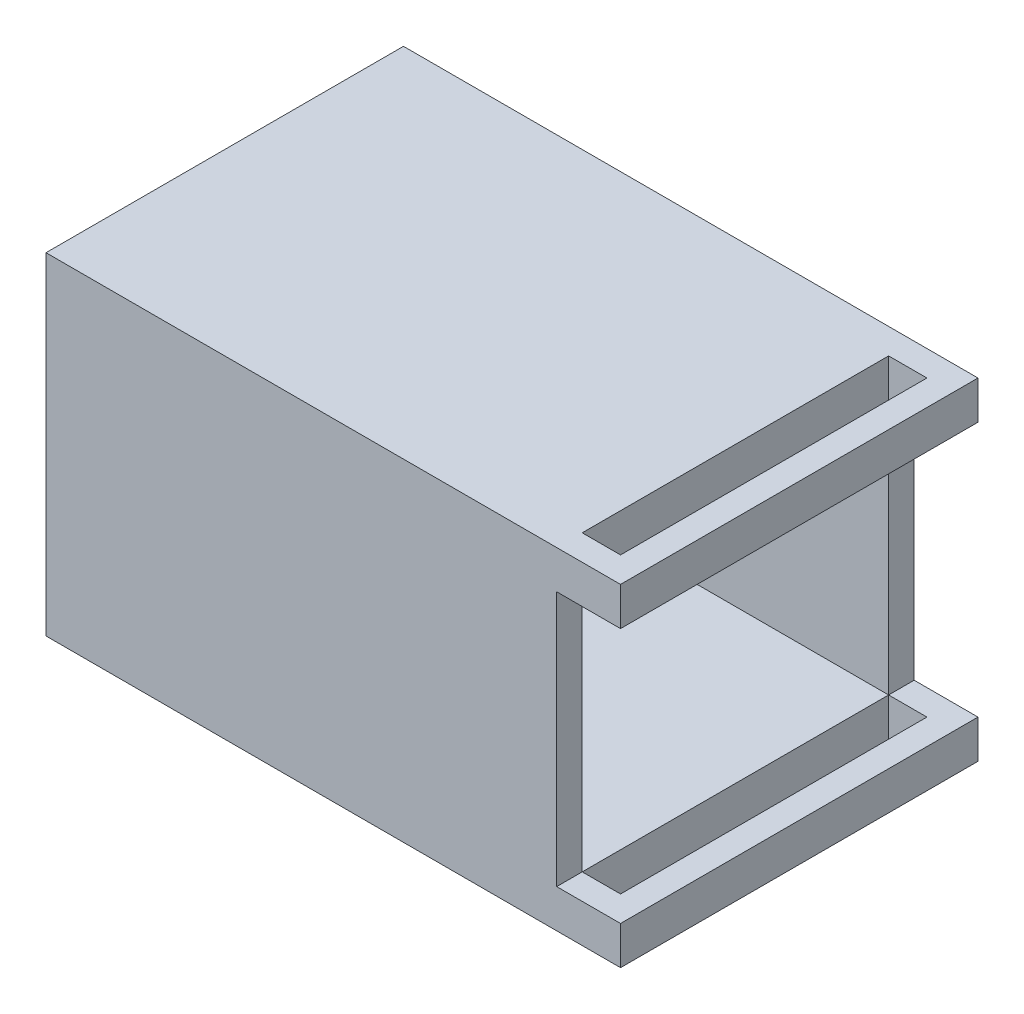
SolidWorks part; units mm, degrees
ref_plane "Front Plane" through (0, 0, 0) normal (0, 0, 1) x (1, 0, 0)
ref_plane "Top Plane" through (0, 0, 0) normal (0, 1, 0) x (1, 0, 0)
ref_plane "Right Plane" through (0, 0, 0) normal (1, 0, 0) x (0, 0, -1)
sketch "Sketch1" plane through (0, 0, 0) normal (0, 1, 0) x (1, 0, 0)
  line L1 (0, 0) -> (45, 0)
  line L2 (0, 0) -> (0, 28)
  line L3 (0, 28) -> (45, 28)
  line L4 (45, 0) -> (45, 28)
  dimension "D1" = 28
  dimension "D2" = 45
extrude "Boss-Extrude1" add sketch "Sketch1" along normal blind 3 contours L2 L1 L4 L3
sketch "Sketch2" plane through (0, 3, 0) normal (0, 1, 0) x (1, 0, 0)
  line L0 (40, 26) -> (40, 28)
  line L1 (0, 28) -> (40, 28)
  line L2 (0, 28) -> (0, 0)
  line L3 (0, 0) -> (40, 0)
  line L5 (2, 26) -> (40, 26)
  line L6 (2, 26) -> (2, 2)
  line L7 (2, 2) -> (40, 2)
  line L9 (40, 2) -> (40, 0)
  line L10 (45, 0) -> (45, 28) construction
  line L11 (0, 0) -> (45, 0) construction
  dimension "D1" = 2
  dimension "D2" = 2
  dimension "D3" = 2
  dimension "D4" = 5
  dimension "D5" = 5
extrude "Boss-Extrude2" add sketch "Sketch2" along normal blind 22 contours L5 L0 L1 L2 L3 L9 L7 L6
sketch "Sketch4" plane through (0, 25, 0) normal (0, 1, 0) x (1, 0, 0)
  line L0 (0, 28) -> (40, 28) construction
  line L1 (0, 28) -> (45, 28)
  line L2 (0, 28) -> (0, 0)
  line L3 (0, 0) -> (45, 0)
  line L4 (45, 28) -> (45, 0)
  line L5 (2, 2) -> (40, 2) construction
  line L6 (40, 26) -> (43, 26)
  line L7 (40, 26) -> (40, 2)
  line L8 (40, 2) -> (43, 2)
  line L9 (43, 26) -> (43, 2)
  dimension "D1" = 2
extrude "Boss-Extrude4" add sketch "Sketch4" against normal blind 2
sketch "Sketch5" plane through (0, 0, 0) normal (-1, 0, 0) x (0, 0, 1)
  line L0 (-18.72, 5.25) -> (-18.72, 6.16)
  line L1 (-17.47, 4) -> (-10.53, 4)
  line L2 (-17.47, 7.41) -> (-10.53, 7.41)
  line L3 (-9.28, 6.16) -> (-9.28, 5.25)
  line L4 (0, 0) -> (-28, 0) construction
  line L5 (-28, 25) -> (-28, 0) construction
  line L6 (0, 25) -> (0, 0) construction
  line L7 (-18.5, 12.5) -> (-9.5, 12.5)
  line L8 (-18.5, 12.5) -> (-18.5, 8.5)
  line L9 (-18.5, 8.5) -> (-9.5, 8.5)
  line L10 (-9.5, 12.5) -> (-9.5, 8.5)
  arc A0 (-18.72, 5.25) -> (-17.47, 4) centre (-17.47, 5.25) ccw
  arc A1 (-17.47, 7.41) -> (-18.72, 6.16) centre (-17.47, 6.16) ccw
  arc A2 (-9.28, 6.16) -> (-10.53, 7.41) centre (-10.53, 6.16) ccw
  arc A3 (-10.53, 4) -> (-9.28, 5.25) centre (-10.53, 5.25) ccw
  dimension "D7" = 1.25
  dimension "D1" = 1.25
  dimension "D2" = 0.91
  dimension "D3" = 6.94
  dimension "D4" = 1.25
  dimension "D5" = 1.25
  dimension "D6" = 6.94
  dimension "D8" = 3.41
  dimension "D9" = 0.91
  dimension "D10" = 4
  dimension "D11" = 9.28
  dimension "D12" = 4
  dimension "D13" = 9
  dimension "D14" = 1.09
  dimension "D15" = 0.22
  dimension "D16" = 0.22
  dimension "D17" = 9.28
extrude "Cut-Extrude1" cut sketch "Sketch5" against normal blind 2
sketch "Sketch6" plane through (0, 3, 0) normal (0, 1, 0) x (1, 0, 0)
  line L0 (45, 0) -> (45, 28) construction
  line L1 (43, 2) -> (40, 2)
  line L2 (43, 2) -> (43, 26)
  line L3 (43, 26) -> (40, 26)
  line L4 (40, 2) -> (40, 26)
  line L5 (40, 0) -> (45, 0) construction
  line L6 (40, 28) -> (45, 28) construction
  line L7 (40, 26) -> (40, 28) construction
  dimension "D1" = 2
  dimension "D2" = 2
  dimension "D3" = 2
extrude "Cut-Extrude2" cut sketch "Sketch6" against normal blind 3
sketch "Sketch7" plane through (0, 25, 0) normal (0, 1, 0) x (1, 0, 0)
  line L1 (0, 0) -> (45, 0)
  line L2 (0, 0) -> (0, 28)
  line L3 (0, 28) -> (45, 28)
  line L4 (45, 0) -> (45, 28)
  line L5 (40, 26) -> (43, 26)
  line L6 (40, 26) -> (40, 2)
  line L7 (40, 2) -> (43, 2)
  line L8 (43, 26) -> (43, 2)
extrude "Boss-Extrude5" add sketch "Sketch7" along normal blind 1
